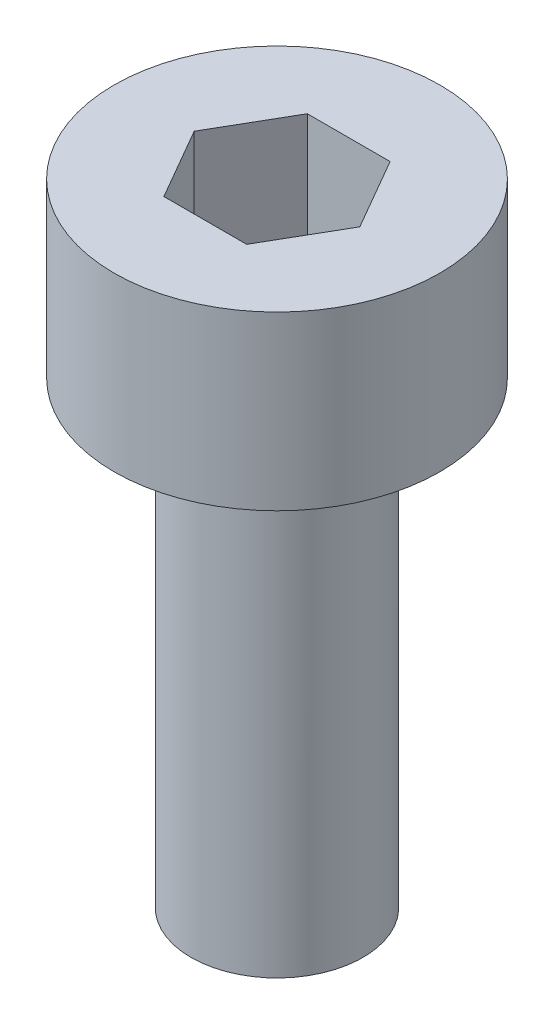
SolidWorks part; units mm, degrees
material "Plain Carbon Steel"
ref_plane "Front Plane" through (0, 0, 0) normal (0, 0, 1) x (1, 0, 0)
ref_plane "Top Plane" through (0, 0, 0) normal (0, 1, 0) x (1, 0, 0)
ref_plane "Right Plane" through (0, 0, 0) normal (1, 0, 0) x (0, 0, -1)
sketch "Sketch1" plane through (0, 0, 0) normal (0, 1, 0) x (1, 0, 0)
  line L1 (0.7217, 1.25) -> (-0.7217, 1.25)
  line L2 (-0.7217, 1.25) -> (-1.4434, 0)
  line L3 (-1.4434, 0) -> (-0.7217, -1.25)
  line L4 (-0.7217, -1.25) -> (0.7217, -1.25)
  line L5 (0.7217, -1.25) -> (1.4434, 0)
  line L6 (1.4434, 0) -> (0.7217, 1.25)
  circle A0 centre (0, 0) radius 1.25 construction
  circle A1 centre (0, 0) radius 2.84
  dimension "D1" = 5.68
  dimension "D2" = 2.5
extrude "Boss-Extrude1" add sketch "Sketch1" along normal blind 3
sketch "Sketch2" plane through (0, 0, 0) normal (0, -1, 0) x (1, 0, 0)
  circle A0 centre (0, 0) radius 1.5
  point P2 (0, 0)
  dimension "D1" = 3
extrude "Boss-Extrude2" add sketch "Sketch2" along normal blind 8
